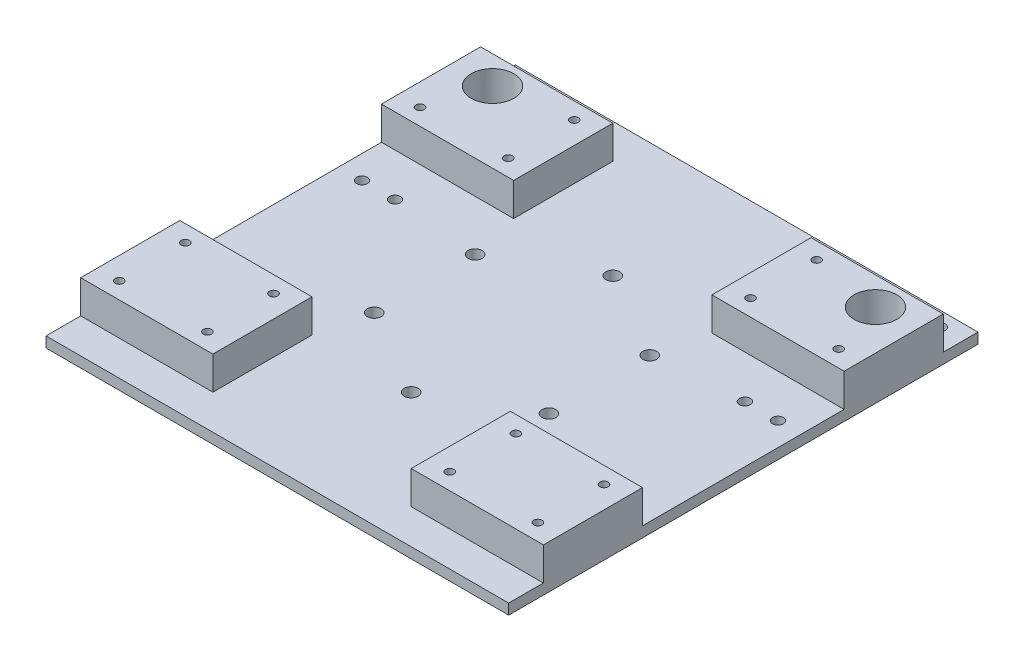
SolidWorks part; units mm, degrees
ref_plane "Front Plane" through (0, 0, 0) normal (0, 0, 1) x (1, 0, 0)
ref_plane "Top Plane" through (0, 0, 0) normal (0, 1, 0) x (1, 0, 0)
ref_plane "Right Plane" through (0, 0, 0) normal (1, 0, 0) x (0, 0, -1)
sketch "Sketch1" plane through (0, 0, 0) normal (0, 1, 0) x (1, 0, 0)
  line L1 (-70, -71) -> (70, -71)
  line L2 (-70, -71) -> (-70, 71)
  line L3 (-70, 71) -> (70, 71)
  line L4 (70, -71) -> (70, 71)
  line L5 (-70, -71) -> (70, 71) construction
  line L6 (-70, 71) -> (70, -71) construction
  point P0 (0, 0)
  dimension "D1" = 140
  dimension "D2" = 142
extrude "Boss-Extrude1" add sketch "Sketch1" along normal blind 3.175
sketch "Sketch2" plane through (0, 3.175, 0) normal (0, 1, 0) x (1, 0, 0)
  line L0 (-45, 30.5) -> (-30, 30.5) construction
  line L1 (-45, -30.5) -> (45, -30.5) construction
  line L2 (-45, -30.5) -> (-45, 30.5) construction
  line L3 (-45, 30.5) -> (45, 30.5) construction
  line L4 (45, -30.5) -> (45, 30.5) construction
  line L5 (-45, -30.5) -> (45, 30.5) construction
  line L6 (-45, 30.5) -> (45, -30.5) construction
  line L7 (-30, 30.5) -> (-30, 60.5) construction
  line L8 (-30, 60.5) -> (-70, 60.5) construction
  line L9 (-30, 60.5) -> (-30, 30.5) construction
  line L10 (-30, 30.5) -> (-70, 30.5) construction
  line L11 (-70, 60.5) -> (-70, 30.5) construction
  line L12 (-30, 60.5) -> (-70, 30.5) construction
  line L13 (-30, 30.5) -> (-70, 60.5) construction
  line L14 (-51.4643, -23.9643) -> (-51.4643, 60.5) construction
  line L15 (-70, 45.5) -> (-30, 45.5) construction
  line L16 (-50, 60.5) -> (-50, 30.5) construction
  line L17 (-57.9286, 52.0357) -> (-57.9286, 62.0357) construction
  line L18 (-62.9286, 66.5357) -> (-52.9286, 66.5357) construction
  line L19 (-67.9286, 62.0357) -> (-47.9286, 62.0357) construction
  line L20 (-67.9286, 62.0357) -> (-67.9286, 22.0357) construction
  line L21 (-67.9286, 22.0357) -> (-47.9286, 22.0357) construction
  line L22 (-47.9286, 62.0357) -> (-47.9286, 22.0357) construction
  line L23 (-67.9286, 62.0357) -> (-47.9286, 22.0357) construction
  line L24 (-67.9286, 22.0357) -> (-47.9286, 62.0357) construction
  line L25 (-67.9286, 17.5357) -> (-47.9286, 17.5357) construction
  line L26 (-67.9286, 17.5357) -> (-67.9286, 66.5357) construction
  line L27 (-67.9286, 66.5357) -> (-47.9286, 66.5357) construction
  line L28 (-47.9286, 17.5357) -> (-47.9286, 66.5357) construction
  line L29 (-67.9286, 17.5357) -> (-47.9286, 66.5357) construction
  line L30 (-67.9286, 66.5357) -> (-47.9286, 17.5357) construction
  line L31 (-67.9286, 14.0357) -> (-47.9286, 14.0357) construction
  line L32 (-67.9286, 14.0357) -> (-67.9286, 70.0357) construction
  line L33 (-67.9286, 70.0357) -> (-47.9286, 70.0357) construction
  line L34 (-47.9286, 14.0357) -> (-47.9286, 70.0357) construction
  line L35 (-67.9286, 14.0357) -> (-47.9286, 70.0357) construction
  line L36 (-67.9286, 70.0357) -> (-47.9286, 14.0357) construction
  line L37 (-67.9286, 42.0357) -> (-47.9286, 42.0357) construction
  line L38 (-45, 30.5) -> (-45, 45.5) construction
  line L39 (-67.9286, 52.0357) -> (-30, 52.0357) construction
  line L40 (-70, 71) -> (-70, -71) construction
  line L41 (0, -7.2462) -> (0, 7.2462) construction
  line L42 (-70, 30.5) -> (-30, 30.5)
  line L43 (-70, 30.5) -> (-70, 60.5)
  line L44 (-70, 60.5) -> (-30, 60.5)
  line L45 (-30, 30.5) -> (-30, 60.5)
  line L46 (-70, 30.5) -> (-30, 60.5) construction
  line L47 (-70, 60.5) -> (-30, 30.5) construction
  line L49 (70, 60.5) -> (30, 60.5)
  line L50 (30, 30.5) -> (30, 60.5)
  line L51 (70, 30.5) -> (30, 30.5)
  line L52 (70, 30.5) -> (70, 60.5)
  line L53 (70, 60.5) -> (30, 30.5) construction
  line L54 (70, 30.5) -> (30, 60.5) construction
  line L55 (-7.2462, 0) -> (7.2462, 0) construction
  line L56 (70, -30.5) -> (70, -60.5)
  line L57 (70, -30.5) -> (30, -30.5)
  line L58 (30, -30.5) -> (30, -60.5)
  line L59 (70, -60.5) -> (30, -60.5)
  line L60 (-70, -60.5) -> (-30, -60.5)
  line L61 (-30, -30.5) -> (-30, -60.5)
  line L62 (-70, -30.5) -> (-30, -30.5)
  line L63 (-70, -30.5) -> (-70, -60.5)
  circle A0 centre (-45, 0) radius 6.4643 construction
  circle A1 centre (-57.9286, 52.0357) radius 6.4643 construction
  circle A2 centre (-57.9286, 52.0357) radius 6.25 construction
  circle A3 centre (-57.9286, 52.0357) radius 2.45 construction
  circle A4 centre (-62.9286, 66.5357) radius 1.65 construction
  circle A5 centre (-52.9286, 66.5357) radius 1.65 construction
  circle A6 centre (-52.9286, 17.5357) radius 1.65 construction
  circle A7 centre (-62.9286, 17.5357) radius 1.65 construction
  circle A13 centre (-36.6667, 55.5) radius 1.25
  circle A14 centre (-36.6667, 35.5) radius 1.25
  circle A15 centre (-63.3333, 35.5) radius 1.25
  circle A16 centre (-63.3333, 55.5) radius 1.25 construction
  circle A17 centre (36.6667, 35.5) radius 1.25
  circle A18 centre (63.3333, 35.5) radius 1.25
  circle A19 centre (63.3333, 55.5) radius 1.25 construction
  circle A20 centre (36.6667, 55.5) radius 1.25
  circle A21 centre (63.3333, -35.5) radius 1.25
  circle A22 centre (63.3333, -55.5) radius 1.25
  circle A23 centre (36.6667, -55.5) radius 1.25
  circle A24 centre (36.6667, -35.5) radius 1.25
  circle A25 centre (-36.6667, -35.5) radius 1.25
  circle A26 centre (-63.3333, -35.5) radius 1.25
  circle A27 centre (-36.6667, -55.5) radius 1.25
  circle A28 centre (-63.3333, -55.5) radius 1.25
  point P0 (0, 0)
  point P9 (-50, 45.5)
  point P22 (-57.9286, 42.0357)
  point P28 (-57.9286, 42.0357)
  point P29 (-57.9286, 62.0357)
  point P34 (-57.9286, 42.0357)
  point P41 (-57.9286, 66.5357)
  point P42 (-57.9286, 66.5357)
  point P51 (-50, 45.5)
  point P78 (50, 45.5)
  dimension "D5" = 12.9286
  dimension "D6" = 12.9286
  dimension "D7" = 12.5
  dimension "D8" = 4.9
  dimension "D15" = 3.3
  dimension "D16" = 2.5
  dimension "D1" = 90
  dimension "D2" = 61
  dimension "D3" = 15
  dimension "D4" = 30
  dimension "D9" = 10
  dimension "D10" = 20
  dimension "D11" = 40
  dimension "D12" = 49
  dimension "D13" = 56
  dimension "D14" = 10
  dimension "D17" = 5
  dimension "D18" = 8.4643
extrude "Boss-Extrude2" add sketch "Sketch2" along normal blind 10 contours L43 L42 L45 L44 | L49 L50 L51 L52 | L60 L61 L62 L63 | L56 L59 L58 L57 | A14 | A15 | A13 | A20 | A17 | A18 | A26 | A25 | A28 | A27 | A24 | A21 | A23 | A22
sketch "Sketch4" plane through (0, 3.175, 0) normal (0, 1, 0) x (1, 0, 0)
  line L0 (-45, 30.5) -> (-30, 30.5) construction
  line L1 (-45, -30.5) -> (45, -30.5) construction
  line L2 (-45, -30.5) -> (-45, 30.5) construction
  line L3 (-45, 30.5) -> (45, 30.5) construction
  line L4 (45, -30.5) -> (45, 30.5) construction
  line L5 (-45, -30.5) -> (45, 30.5) construction
  line L6 (-45, 30.5) -> (45, -30.5) construction
  line L7 (-30, 30.5) -> (-30, 60.5) construction
  line L8 (-30, 60.5) -> (-70, 60.5) construction
  line L9 (-30, 60.5) -> (-30, 30.5) construction
  line L10 (-30, 30.5) -> (-70, 30.5) construction
  line L11 (-70, 60.5) -> (-70, 30.5) construction
  line L12 (-30, 60.5) -> (-70, 30.5) construction
  line L13 (-30, 30.5) -> (-70, 60.5) construction
  line L14 (-51.4643, -23.9643) -> (-51.4643, 60.5) construction
  line L15 (-70, 45.5) -> (-30, 45.5) construction
  line L16 (-50, 60.5) -> (-50, 30.5) construction
  line L17 (-57.9286, 52.0357) -> (-57.9286, 62.0357) construction
  line L18 (-62.9286, 66.5357) -> (-52.9286, 66.5357) construction
  line L19 (-67.9286, 62.0357) -> (-47.9286, 62.0357) construction
  line L20 (-67.9286, 62.0357) -> (-67.9286, 22.0357) construction
  line L21 (-67.9286, 22.0357) -> (-47.9286, 22.0357) construction
  line L22 (-47.9286, 62.0357) -> (-47.9286, 22.0357) construction
  line L23 (-67.9286, 62.0357) -> (-47.9286, 22.0357) construction
  line L24 (-67.9286, 22.0357) -> (-47.9286, 62.0357) construction
  line L25 (-67.9286, 17.5357) -> (-47.9286, 17.5357) construction
  line L26 (-67.9286, 17.5357) -> (-67.9286, 66.5357) construction
  line L27 (-67.9286, 66.5357) -> (-47.9286, 66.5357) construction
  line L28 (-47.9286, 17.5357) -> (-47.9286, 66.5357) construction
  line L29 (-67.9286, 17.5357) -> (-47.9286, 66.5357) construction
  line L30 (-67.9286, 66.5357) -> (-47.9286, 17.5357) construction
  line L31 (-67.9286, 14.0357) -> (-47.9286, 14.0357) construction
  line L32 (-67.9286, 14.0357) -> (-67.9286, 70.0357) construction
  line L33 (-67.9286, 70.0357) -> (-47.9286, 70.0357) construction
  line L34 (-47.9286, 14.0357) -> (-47.9286, 70.0357) construction
  line L35 (-67.9286, 14.0357) -> (-47.9286, 70.0357) construction
  line L36 (-67.9286, 70.0357) -> (-47.9286, 14.0357) construction
  line L37 (-67.9286, 42.0357) -> (-47.9286, 42.0357) construction
  line L38 (-45, 30.5) -> (-45, 45.5) construction
  line L39 (-67.9286, 52.0357) -> (-30, 52.0357) construction
  line L40 (-70, 30.5) -> (-30, 30.5) construction
  line L41 (-70, 30.5) -> (-70, 60.5) construction
  line L42 (-70, 60.5) -> (-30, 60.5) construction
  line L43 (-30, 30.5) -> (-30, 60.5) construction
  line L44 (-70, 30.5) -> (-30, 60.5) construction
  line L45 (-70, 60.5) -> (-30, 30.5) construction
  line L50 (-70, 30.5) -> (-70, 60.5) construction
  line L51 (0, -7.2462) -> (0, 7.2462) construction
  circle A0 centre (-45, 0) radius 6.4643 construction
  circle A1 centre (-57.9286, 52.0357) radius 6.4643
  circle A2 centre (-57.9286, 52.0357) radius 6.25 construction
  circle A3 centre (-57.9286, 52.0357) radius 2.45 construction
  circle A4 centre (-62.9286, 66.5357) radius 1.65
  circle A5 centre (-52.9286, 66.5357) radius 1.65
  circle A6 centre (-52.9286, 17.5357) radius 1.65
  circle A7 centre (-62.9286, 17.5357) radius 1.65
  circle A8 centre (-36.6667, 55.5) radius 1.25 construction
  circle A9 centre (-36.6667, 35.5) radius 1.25 construction
  circle A10 centre (-63.3333, 35.5) radius 1.25 construction
  circle A11 centre (-63.3333, 55.5) radius 1.25 construction
  circle A12 centre (52.9286, 66.5357) radius 1.65
  circle A13 centre (62.9286, 66.5357) radius 1.65
  circle A14 centre (57.9286, 52.0357) radius 6.4643
  circle A15 centre (52.9286, 17.5357) radius 1.65
  circle A16 centre (62.9286, 17.5357) radius 1.65
  point P0 (0, 0)
  point P9 (-50, 45.5)
  point P22 (-57.9286, 42.0357)
  point P28 (-57.9286, 42.0357)
  point P29 (-57.9286, 62.0357)
  point P34 (-57.9286, 42.0357)
  point P41 (-57.9286, 66.5357)
  point P42 (-57.9286, 66.5357)
  point P51 (-50, 45.5)
  dimension "D5" = 12.9286
  dimension "D6" = 12.9286
  dimension "D7" = 12.5
  dimension "D8" = 4.9
  dimension "D14" = 3.3
  dimension "D15" = 2.5
  dimension "D1" = 90
  dimension "D2" = 61
  dimension "D3" = 15
  dimension "D4" = 30
  dimension "D9" = 10
  dimension "D10" = 40
  dimension "D11" = 49
  dimension "D12" = 56
  dimension "D13" = 10
  dimension "D16" = 5
  dimension "D17" = 8.4643
  dimension "D18" = 20
extrude "Cut-Extrude1" cut sketch "Sketch4" against normal up to surface and the other way up to surface contours A14 | A16 | A4 | A5 | A1 | A7 | A6 | A12 | A13 | A15 up to face at (0, 0, 0) other way up to face at (63.3333, 13.175, -36.75)
sketch "Sketch5" plane through (0, 3.175, 0) normal (0, 1, 0) x (1, 0, 0)
  line L0 (0, 0) -> (0, 30.525) construction
  line L1 (0, 0) -> (0, 30.525) construction
  line L2 (0, 0) -> (26.4354, 15.2625) construction
  circle A0 centre (0, 0) radius 40 construction
  circle A1 centre (0, 0) radius 30.525 construction
  circle A2 centre (0, 30.525) radius 2.1
  circle A8 centre (26.4354, 15.2625) radius 2.1
  circle A9 centre (26.4354, -15.2625) radius 2.1
  circle A10 centre (0, -30.525) radius 2.1
  circle A11 centre (-26.4354, -15.2625) radius 2.1
  circle A12 centre (-26.4354, 15.2625) radius 2.1
  dimension "D1" = 61.05
  dimension "D2" = 4.2
  dimension "D4" = 80
  dimension "D3" = 6
  dimension "D5" = 60
extrude "Cut-Extrude2" cut sketch "Sketch5" against normal up to surface (3.175 mm away) contours A12 | A2 | A8 | A9 | A11 | A10 up to face at (62.9286, 0, -68.1857)
sketch "Sketch6" plane through (0, 3.175, 0) normal (0, 1, 0) x (1, 0, 0)
  line L0 (-50, 30.5) -> (-50, 60.5) construction
  line L1 (-70, 30.5) -> (-30, 30.5) construction
  line L2 (-70, 60.5) -> (-30, 60.5) construction
  line L3 (-70, 45.5) -> (-30, 45.5) construction
  line L4 (-70, 30.5) -> (-70, 60.5) construction
  line L5 (-30, 30.5) -> (-30, 60.5) construction
  line L6 (0, -7.2462) -> (0, 7.2462) construction
  line L7 (-7.2462, 0) -> (7.2462, 0) construction
  circle A0 centre (-36.6667, 35.5) radius 1.25
  circle A1 centre (-36.6667, 35.5) radius 1.25 construction
  circle A2 centre (-63.3333, 35.5) radius 1.25
  circle A3 centre (-36.6667, 55.5) radius 1.25
  circle A4 centre (-63.3333, 55.5) radius 1.25 construction
  circle A5 centre (36.6667, 55.5) radius 1.25
  circle A6 centre (36.6667, 35.5) radius 1.25
  circle A7 centre (63.3333, 35.5) radius 1.25
  circle A8 centre (63.3333, 55.5) radius 1.25 construction
  circle A9 centre (63.3333, -55.5) radius 1.25
  circle A10 centre (63.3333, -35.5) radius 1.25
  circle A11 centre (36.6667, -35.5) radius 1.25
  circle A12 centre (36.6667, -55.5) radius 1.25
  circle A13 centre (-36.6667, -55.5) radius 1.25
  circle A14 centre (-63.3333, -55.5) radius 1.25
  circle A15 centre (-63.3333, -35.5) radius 1.25
  circle A16 centre (-36.6667, -35.5) radius 1.25
extrude "Cut-Extrude3" cut sketch "Sketch6" against normal up to surface (3.175 mm away) up to face at (0, 0, 28.425)
sketch "Sketch7" plane through (0, 13.175, 0) normal (0, 1, 0) x (1, 0, 0)
  line L0 (-70, -60.5) -> (-30, -60.5) construction
  line L2 (-45, -39.0357) -> (-57.9286, -39.0357) construction
  line L3 (-57.9286, 52.0357) -> (-57.9286, -51.9643) construction
  line L5 (-70, -30.5) -> (-70, -60.5) construction
  circle A0 centre (-57.9286, -51.9643) radius 6.4643 construction
  circle A1 centre (-57.9286, -51.9643) radius 4.8125
  circle A2 centre (-45, -39.0357) radius 6.4643 construction
  circle A3 centre (-45, -39.0357) radius 4.8125
  circle A4 centre (-57.9286, -51.9643) radius 8.6995 construction
  circle A5 centre (-45, -39.0357) radius 8.6995 construction
  dimension "D2" = 12.9286
  dimension "D3" = 9.625
  dimension "D6" = 12.9286
  dimension "D7" = 9.625
  dimension "D8" = 17.399
  dimension "D9" = 17.399
  dimension "D10" = 7.2589
  dimension "D11" = 12.0714
  dimension "D1" = 8.5357
  dimension "D4" = 12.9286
  dimension "D5" = 12.9286
